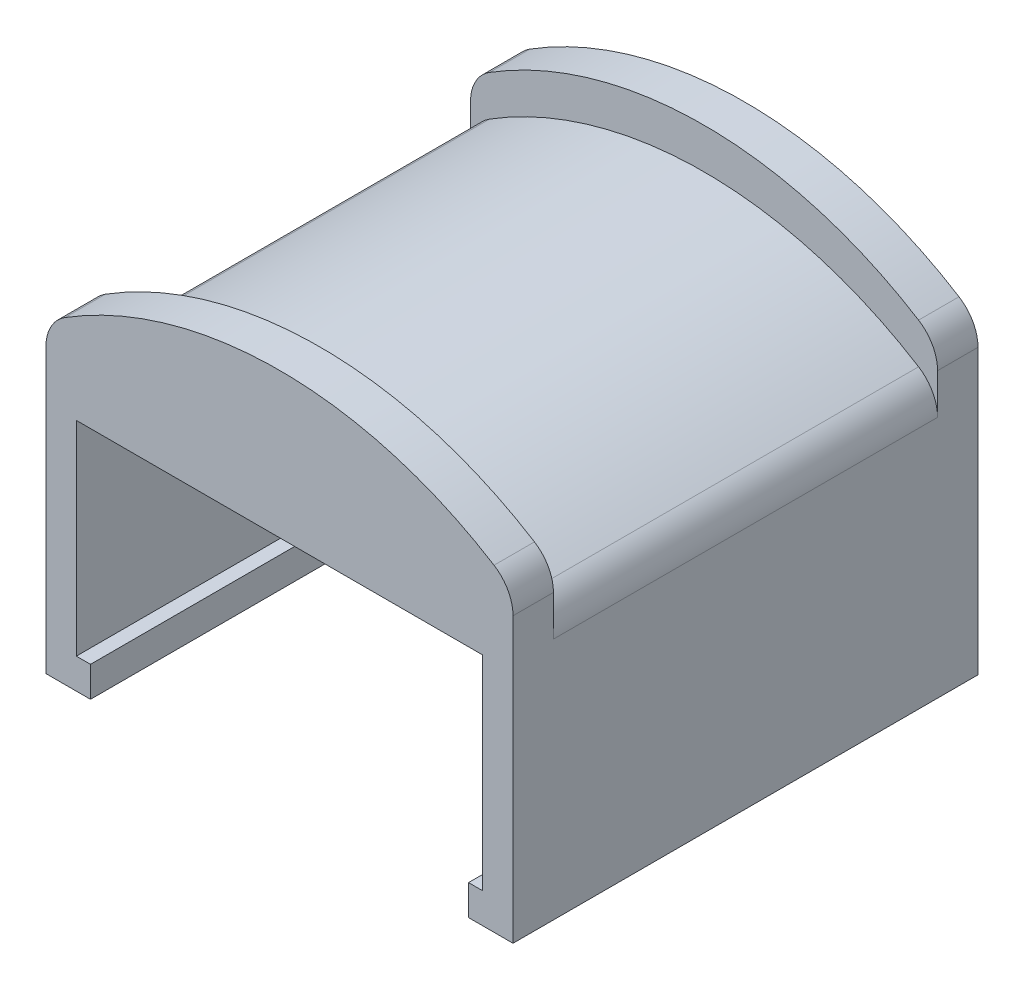
SolidWorks part; units mm, degrees
ref_plane "Front Plane" through (0, 0, 0) normal (0, 0, 1) x (1, 0, 0)
ref_plane "Top Plane" through (0, 0, 0) normal (0, 1, 0) x (1, 0, 0)
ref_plane "Right Plane" through (0, 0, 0) normal (1, 0, 0) x (0, 0, -1)
sketch "Sketch1" plane through (0, 0, 0) normal (0, 0, 1) x (1, 0, 0)
  line L0 (-25.527, 0) -> (25.527, 0)
  line L1 (-25.527, 0) -> (-25.527, -25.654)
  line L2 (25.527, 0) -> (25.527, -25.654)
  line L3 (-25.527, -25.654) -> (-23.749, -25.654)
  line L4 (-23.749, -25.654) -> (-23.749, -29.464)
  line L5 (-23.749, -29.464) -> (-29.337, -29.464)
  line L6 (-29.337, -29.464) -> (-29.337, 3.81)
  line L7 (25.527, -25.654) -> (23.749, -25.654)
  line L8 (23.749, -25.654) -> (23.749, -29.464)
  line L9 (23.749, -29.464) -> (29.337, -29.464)
  line L10 (29.337, -29.464) -> (29.337, 3.81)
  arc A0 (-29.337, 3.81) -> (29.337, 3.81) centre (0, -37.6626) cw
  point P3 (0, 0)
  dimension "D10" = 50.8
  dimension "D11" = 1.778
  dimension "D1" = 51.054
  dimension "D2" = 25.654
  dimension "D3" = 25.654
  dimension "D4" = 3.81
  dimension "D5" = 5.588
  dimension "D6" = 3.81
  dimension "D7" = 3.81
  dimension "D8" = 5.588
  dimension "D9" = 3.81
  dimension "D12" = 1.778
extrude "Boss-Extrude1" add sketch "Sketch1" along normal mid plane 48.26
sketch "Sketch2" plane through (0, 0, 24.13) normal (0, 0, 1) x (1, 0, 0)
  line L0 (29.337, -29.464) -> (29.337, 8.89)
  line L1 (-29.337, -29.464) -> (-29.337, 8.89)
  line L11 (-25.527, -25.654) -> (-25.527, 0)
  line L12 (-25.527, 0) -> (25.527, 0)
  line L13 (25.527, 0) -> (25.527, -25.654)
  line L14 (25.527, -25.654) -> (23.749, -25.654)
  line L15 (23.749, -25.654) -> (23.749, -29.464)
  line L16 (23.749, -29.464) -> (29.337, -29.464)
  line L17 (29.337, -29.464) -> (29.337, 3.81)
  line L18 (-29.337, 3.81) -> (-29.337, -29.464)
  line L19 (-29.337, -29.464) -> (-23.749, -29.464)
  line L20 (-23.749, -29.464) -> (-23.749, -25.654)
  line L21 (-23.749, -25.654) -> (-25.527, -25.654)
  line L22 (-25.527, -25.654) -> (-25.527, 0)
  line L23 (-25.527, 0) -> (25.527, 0)
  line L24 (25.527, 0) -> (25.527, -25.654)
  line L25 (25.527, -25.654) -> (23.749, -25.654)
  line L26 (23.749, -25.654) -> (23.749, -29.464)
  line L27 (23.749, -29.464) -> (29.337, -29.464)
  line L30 (-29.337, -29.464) -> (-23.749, -29.464)
  line L31 (-23.749, -29.464) -> (-23.749, -25.654)
  line L32 (-23.749, -25.654) -> (-25.527, -25.654)
  arc A0 (-29.337, 8.89) -> (29.337, 8.89) centre (0, -32.5826) cw
  arc A1 (29.337, 3.81) -> (-29.337, 3.81) centre (0, -37.6626) ccw
  dimension "D2" = 5.08
  dimension "D4" = 50.8
  dimension "D3" = 5.08
  dimension "D1" = 0
extrude "Boss-Extrude2" add sketch "Sketch2" along normal blind 5.08
pattern_linear "LPattern1" count 2 spacing 53.34 along (0, 0, -1) of "Boss-Extrude2"
fillet "Fillet1" radius 5.08 6 edges at (-29.337, 8.89, -26.67) (29.337, 8.89, -26.67) (-29.337, 3.81, 0) (-29.337, 8.89, 26.67) (29.337, 8.89, 26.67) (29.337, 3.81, 0)
